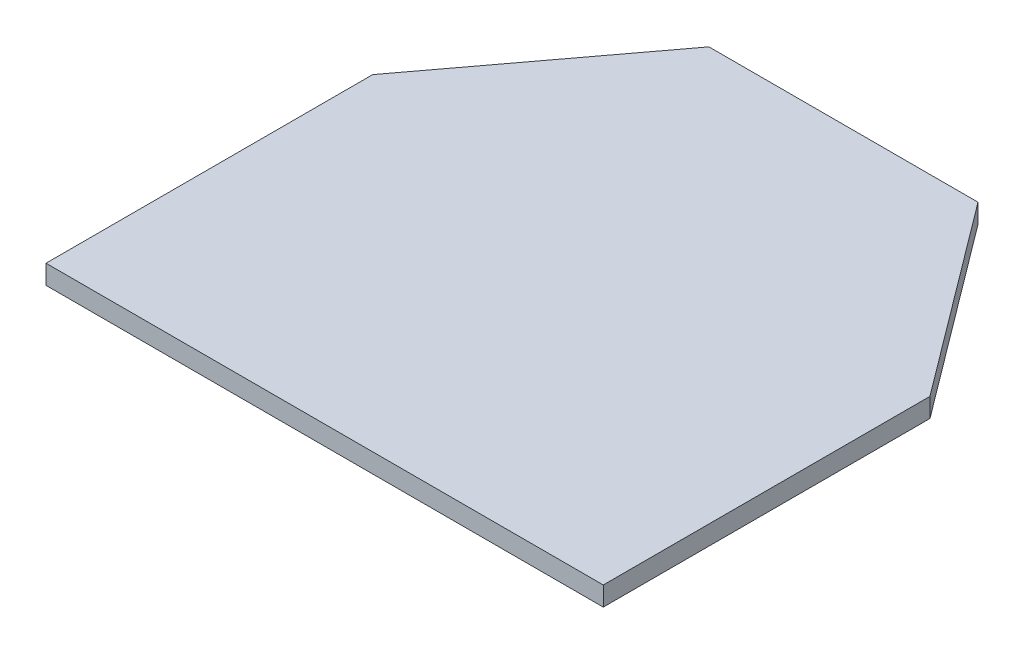
SolidWorks part; units mm, degrees
ref_plane "Front Plane" through (0, 0, 0) normal (0, 0, 1) x (1, 0, 0)
ref_plane "Top Plane" through (0, 0, 0) normal (0, 1, 0) x (1, 0, 0)
ref_plane "Right Plane" through (0, 0, 0) normal (1, 0, 0) x (0, 0, -1)
sketch "Sketch2" plane through (0, 0, 0) normal (0, 1, 0) x (1, 0, 0)
  line L0 (-15.6894, -1.6095) -> (-15.6894, 15.3905)
  line L1 (-15.6894, -1.6095) -> (13.3106, -1.6095)
  line L2 (-8.1894, 25.3905) -> (5.8106, 25.3905)
  line L3 (13.3106, -1.6095) -> (13.3106, 15.3905)
  line L4 (-15.6894, 15.3905) -> (-8.1894, 25.3905)
  line L5 (13.3106, 15.3905) -> (5.8106, 25.3905)
  dimension "D1" = 7.5
  dimension "D3" = 17
  dimension "D4" = 17
  dimension "D5" = 14
extrude "Boss-Extrude1" add sketch "Sketch2" along normal blind 1
